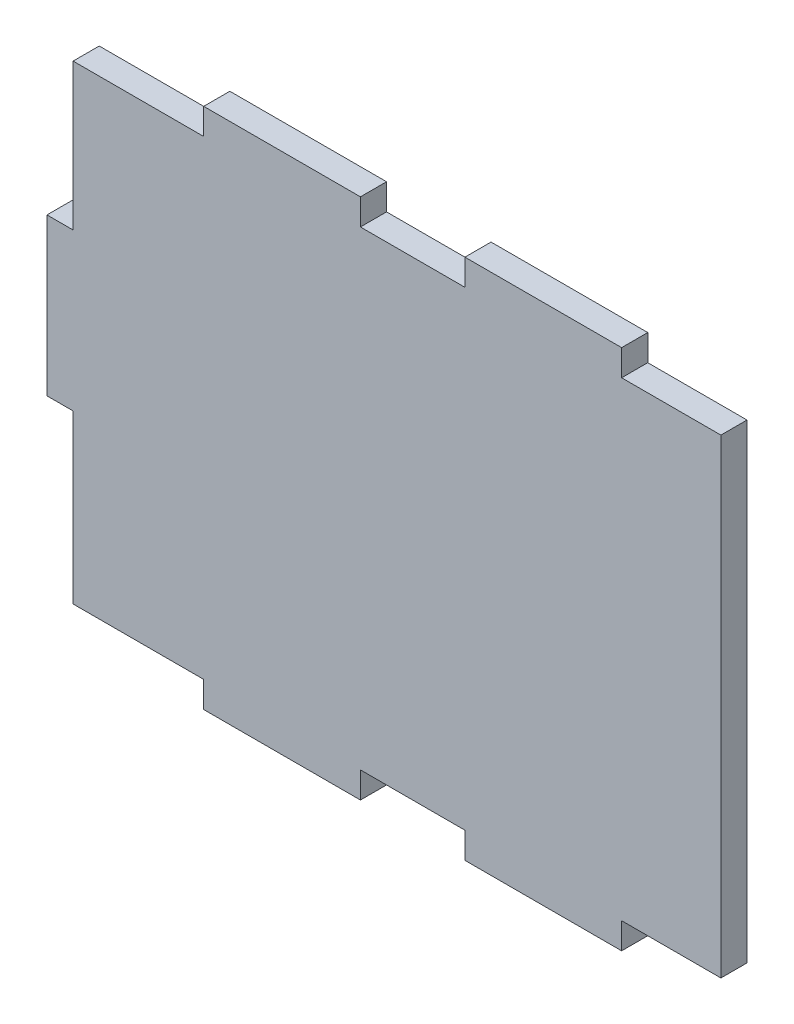
SolidWorks part; units mm, degrees
ref_plane "Front Plane" through (0, 0, 0) normal (0, 0, 1) x (1, 0, 0)
ref_plane "Top Plane" through (0, 0, 0) normal (0, 1, 0) x (1, 0, 0)
ref_plane "Right Plane" through (0, 0, 0) normal (1, 0, 0) x (0, 0, -1)
sketch "Sketch1" plane through (0, 0, 0) normal (0, 0, 1) x (1, 0, 0)
  line L45 (-69, 245) -> (-69, 250)
  line L46 (-69, 250) -> (-99, 250)
  line L47 (-1126.2657, 244.9504) -> (-124, 244.9504) construction
  line L48 (-99, 250) -> (-99, 245)
  line L50 (0, 150) -> (0, 250) construction
  line L51 (-19, 245) -> (-19, 250)
  line L52 (-19, 250) -> (-49, 250)
  line L53 (-49, 250) -> (-49, 245)
  line L54 (-49, 150) -> (-19, 150)
  line L55 (-19, 150) -> (-19, 155)
  line L57 (-49, 155) -> (-49, 150)
  line L58 (-99, 150) -> (-69, 150)
  line L59 (-69, 150) -> (-69, 155)
  line L61 (-99, 155) -> (-99, 150)
  line L63 (-124, 217) -> (-129, 217)
  line L64 (-129, 217) -> (-129, 187)
  line L65 (-129, 187) -> (-124, 187)
  line L66 (-124, 155) -> (-124, 187)
  line L67 (-124, 155) -> (-99, 155)
  line L68 (-69, 155) -> (-49, 155)
  line L69 (-19, 155) -> (0, 155)
  line L70 (0, 155) -> (0, 245)
  line L71 (0, 245) -> (-19, 245)
  line L72 (-49, 245) -> (-69, 245)
  line L73 (-99, 245) -> (-124, 245)
  line L74 (-124, 245) -> (-124, 217)
  line L75 (0, 244.9504) -> (1123.743, 244.9504) construction
extrude "Boss-Extrude1" add sketch "Sketch1" along normal blind 5
